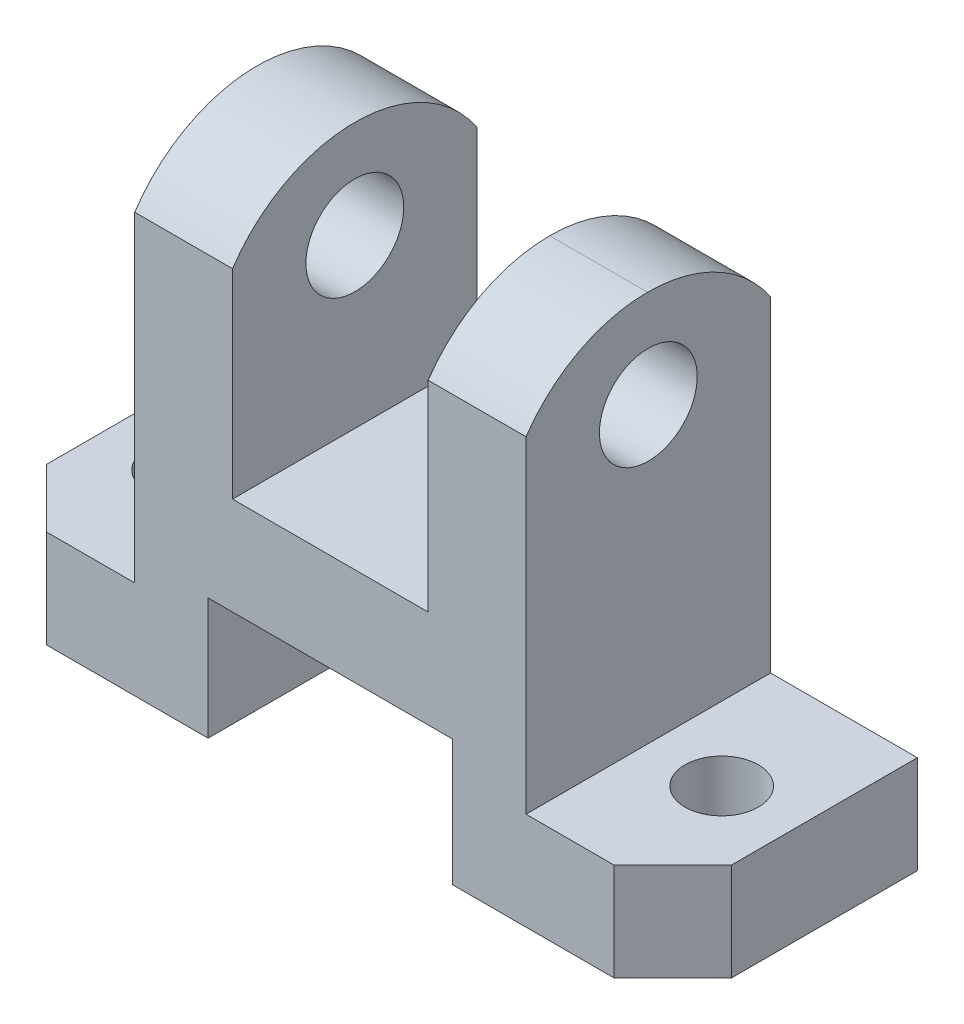
SolidWorks part; units mm, degrees
ref_plane "Front Plane" through (0, 0, 0) normal (0, 0, 1) x (1, 0, 0)
ref_plane "Top Plane" through (0, 0, 0) normal (0, 1, 0) x (1, 0, 0)
ref_plane "Right Plane" through (0, 0, 0) normal (1, 0, 0) x (0, 0, -1)
sketch "Sketch2" plane through (0, 0, 0) normal (0, 0, 1) x (1, 0, 0)
  line L0 (-77.6359, 41.7128) -> (-64.9359, 41.7128)
  line L1 (-64.9359, 41.7128) -> (-64.9359, 6.6836)
  line L2 (-64.9359, 6.6836) -> (-39.5359, 6.6836)
  line L3 (-39.5359, 6.6836) -> (-39.5359, 41.1063)
  line L4 (-39.5359, 41.1063) -> (-26.8359, 41.1063)
  line L5 (-26.8359, 41.1063) -> (-26.8359, -9.6937)
  line L6 (-26.8359, -9.6937) -> (-7.7859, -9.6937)
  line L7 (-7.7859, -9.6937) -> (-7.7859, -22.3937)
  line L8 (-7.7859, -22.3937) -> (-36.3609, -22.3937)
  line L9 (-36.3609, -22.3937) -> (-36.3609, -6.0164)
  line L10 (-36.3609, -6.0164) -> (-68.1109, -6.0164)
  line L11 (-68.1109, -6.0164) -> (-68.1109, -21.7872)
  line L12 (-68.1109, -21.7872) -> (-96.6859, -21.7872)
  line L13 (-96.6859, -21.7872) -> (-96.6859, -9.0872)
  line L14 (-77.6359, 41.7128) -> (-77.6359, -9.0872)
  line L15 (-77.6359, -9.0872) -> (-96.6859, -9.0872)
  dimension "D1" = 50.8
  dimension "D2" = 50.8
  dimension "D3" = 12.7
  dimension "D4" = 12.7
  dimension "D5" = 19.05
  dimension "D6" = 19.05
  dimension "D7" = 12.7
  dimension "D8" = 12.7
  dimension "D9" = 12.7
  dimension "D10" = 25.4
  dimension "D11" = 31.75
extrude "Boss-Extrude1" add sketch "Sketch2" along normal blind 31.75
sketch "Sketch3" plane through (0, -9.6937, 0) normal (0, 1, 0) x (1, 0, 0)
  line L0 (-7.7859, -31.75) -> (-7.7859, -24.13)
  line L1 (-7.7859, -31.75) -> (-7.7859, 0) construction
  line L2 (-7.7859, -31.75) -> (-15.4059, -31.75)
  line L3 (-7.7859, -31.75) -> (-26.8359, -31.75) construction
  line L4 (-7.7859, -24.13) -> (-15.4059, -31.75)
  line L5 (-96.6859, -31.75) -> (-89.0659, -31.75)
  line L6 (-77.6359, -31.75) -> (-96.6859, -31.75) construction
  line L7 (-96.6859, -31.75) -> (-96.6859, -24.13)
  line L8 (-96.6859, -31.75) -> (-96.6859, 0) construction
  line L9 (-96.6859, -24.13) -> (-89.0659, -31.75)
  line L10 (-96.6859, -24.13) -> (-89.0659, -31.75)
  line L11 (-96.6859, -31.75) -> (-96.6859, -24.13)
  line M8 (-26.8359, -31.75) -> (-7.7859, -31.75)
  line M9 (-7.7859, -31.75) -> (-7.7859, 0)
  dimension "D1" = 7.62
  dimension "D2" = 7.62
extrude "Cut-Extrude2" cut sketch "Sketch3" against normal through all and the other way through all contours L9 L7 L5 | L4 M9 M8
sketch "Sketch4" plane through (-26.8359, 0, 0) normal (1, 0, 0) x (0, 0, -1)
  line L0 (-31.75, -9.6937) -> (0, -9.6937) construction
  circle A0 centre (-15.875, 28.4063) radius 6.35
  dimension "D2" = 12.7
  dimension "D1" = 38.1
extrude "Cut-Extrude3" cut sketch "Sketch4" against normal through all
sketch "Sketch8" plane through (-26.8359, 0, 0) normal (1, 0, 0) x (0, 0, -1)
  line L2 (0, 32.5865) -> (0, 41.1063)
  line L3 (-31.75, 41.1063) -> (-31.75, 32.5865)
  line L5 (0, 32.5865) -> (0, 41.1063)
  line L6 (0, 41.1063) -> (-31.75, 41.1063)
  line L9 (-31.75, 32.5865) -> (-31.75, 41.1063)
  line L10 (0, 32.5865) -> (0, 41.1063)
  line L13 (-31.75, 41.1063) -> (0, 41.1063)
  line L14 (-31.75, 41.1063) -> (-31.75, 32.5865)
  line L16 (-31.75, -9.6937) -> (-31.75, 41.1063) construction
  line L18 (0, 41.1063) -> (0, 32.5865)
  line L19 (0, -9.6937) -> (0, 41.1063) construction
  arc A4 (0, 32.5865) -> (-31.75, 32.5865) centre (-15.875, 22.0563) ccw
  point P2 (0, 0)
  point P3 (0, 0)
  dimension "D1" = 38.1
sketch "Sketch9" plane through (-26.8359, 0, 0) normal (1, 0, 0) x (0, 0, -1)
  line L0 (-31.75, 32.5865) -> (-31.75, 41.1063)
  line L1 (0, 41.1063) -> (0, 32.5865)
  line L2 (-31.75, 41.1063) -> (-31.75, 32.5865)
  line L3 (-15.875, 41.1063) -> (-31.75, 41.1063)
  line L4 (0, 41.1063) -> (0, 32.5865)
  line L5 (-31.75, 41.1063) -> (0, 41.1063)
  line L6 (-31.75, 32.5865) -> (-31.75, 41.1063)
  circle A2 centre (-15.9805, 22.0563) radius 19.05
  dimension "D1" = 38.1
extrude "Cut-Extrude13" cut sketch "Sketch9" against normal blind 31.75 contours A2 L5 L2
sketch "Sketch10" plane through (-26.8359, 0, 0) normal (1, 0, 0) x (0, 0, -1)
  line L0 (0, 32.5865) -> (0, 41.1063)
  line L1 (0, 41.1063) -> (-15.9805, 41.1063)
  arc A1 (-15.9805, 41.1063) -> (0, 32.5865) centre (-15.9805, 21.859) cw
extrude "Cut-Extrude18" cut sketch "Sketch10" against normal blind 25.4 contours A1 L0 L1
sketch "Sketch11" plane through (-77.6359, 0, 0) normal (-1, 0, 0) x (0, 0, 1)
  line L0 (0, 41.1063) -> (31.75, 41.1063)
extrude "Cut-Extrude22" cut sketch "Sketch11" against normal blind 25.4 and the other way through all
sketch "Sketch13" plane through (-77.6359, 0, 0) normal (-1, 0, 0) x (0, 0, 1)
  line L0 (0, 41.1063) -> (31.75, 41.1063)
  line L7 (31.75, 41.1063) -> (31.75, 29.3399)
  line L8 (31.75, 41.1063) -> (31.75, -9.0872) construction
  line L9 (0, 41.1063) -> (0, 32.5865)
  line L10 (0, 41.1063) -> (0, -9.0872) construction
  line L12 (15.875, 41.1063) -> (31.75, 41.1063)
  line L13 (31.75, 32.5865) -> (31.75, 41.1063)
  line L14 (0, 32.5865) -> (0, 41.1063)
  line L15 (15.875, 41.1063) -> (0, 41.1063)
  arc A2 (31.75, 32.5865) -> (0, 32.5865) centre (15.875, 22.0563) ccw
  line M3 (31.75, 41.1063) -> (0, 41.1063)
  line M4 (0, 41.1063) -> (0, -9.0872)
  dimension "D1" = 38.1
extrude "Cut-Extrude23" cut sketch "Sketch13" against normal blind 25.4 contours A2 L7 M3 | A2 L0 M4
sketch "Sketch14" plane through (0, -9.0872, 0) normal (0, 1, 0) x (1, 0, 0)
  line L0 (-7.7859, 0) -> (-26.8359, 0) construction
  line L1 (-7.7859, -24.13) -> (-7.7859, 0) construction
  circle A0 centre (-17.3109, -15.875) radius 4.7625
  dimension "D3" = 9.525
  dimension "D1" = 15.875
  dimension "D2" = 9.525
extrude "Cut-Extrude24" cut sketch "Sketch14" against normal through all
sketch "Sketch15" plane through (0, -9.0872, 0) normal (0, 1, 0) x (1, 0, 0)
  line L0 (-96.6859, -24.13) -> (-96.6859, 0) construction
  line L1 (-77.6359, 0) -> (-96.6859, 0) construction
  circle A0 centre (-87.1609, -15.875) radius 4.7625
  dimension "D1" = 9.525
  dimension "D2" = 9.525
  dimension "D3" = 15.875
extrude "Cut-Extrude25" cut sketch "Sketch15" against normal through all
